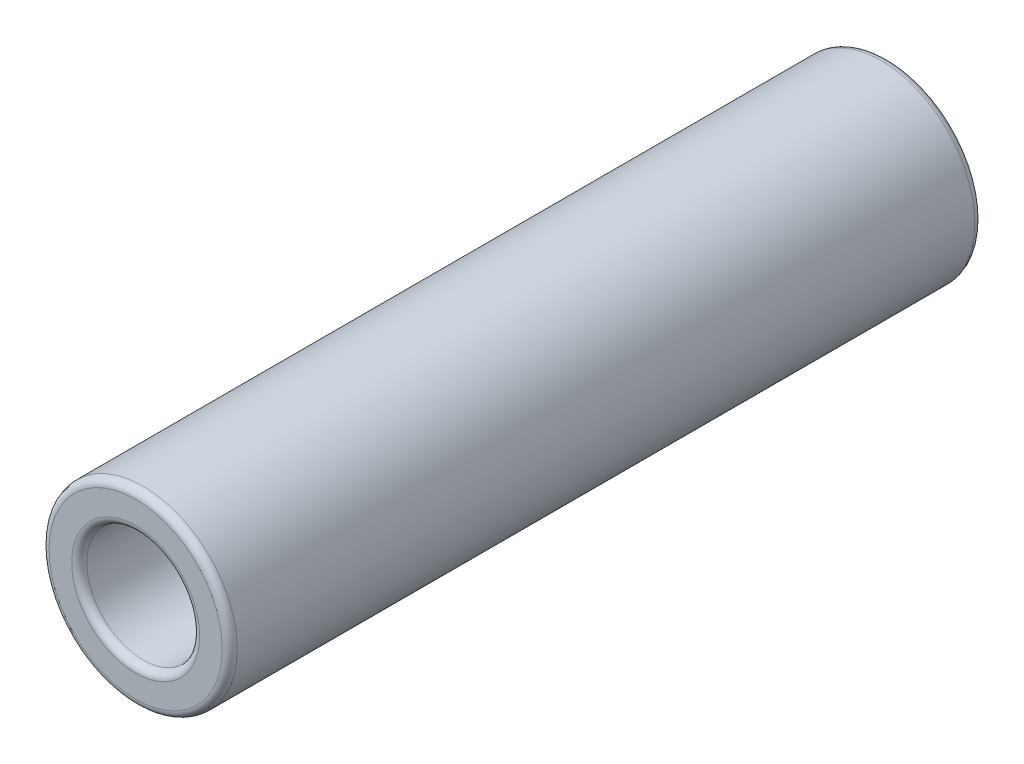
SolidWorks part; units mm, degrees
material "1100-H16 Rod (SS)"
ref_plane "Front Plane" through (0, 0, 0) normal (0, 0, 1) x (1, 0, 0)
ref_plane "Top Plane" through (0, 0, 0) normal (0, 1, 0) x (1, 0, 0)
ref_plane "Right Plane" through (0, 0, 0) normal (1, 0, 0) x (0, 0, -1)
sketch "Sketch1" plane through (0, 0, 0) normal (0, 0, 1) x (1, 0, 0)
  circle A0 centre (0, 0) radius 6.25
  circle A1 centre (0, 0) radius 3.75
  dimension "D1" = 7.5
  dimension "D2" = 12.5
extrude "Boss-Extrude1" add sketch "Sketch1" along normal blind 50
fillet "Fillet1" radius 0.5 4 edges at (3.75, 0, 50) (6.25, 0, 50) (3.75, 0, 0) (6.25, 0, 0)
